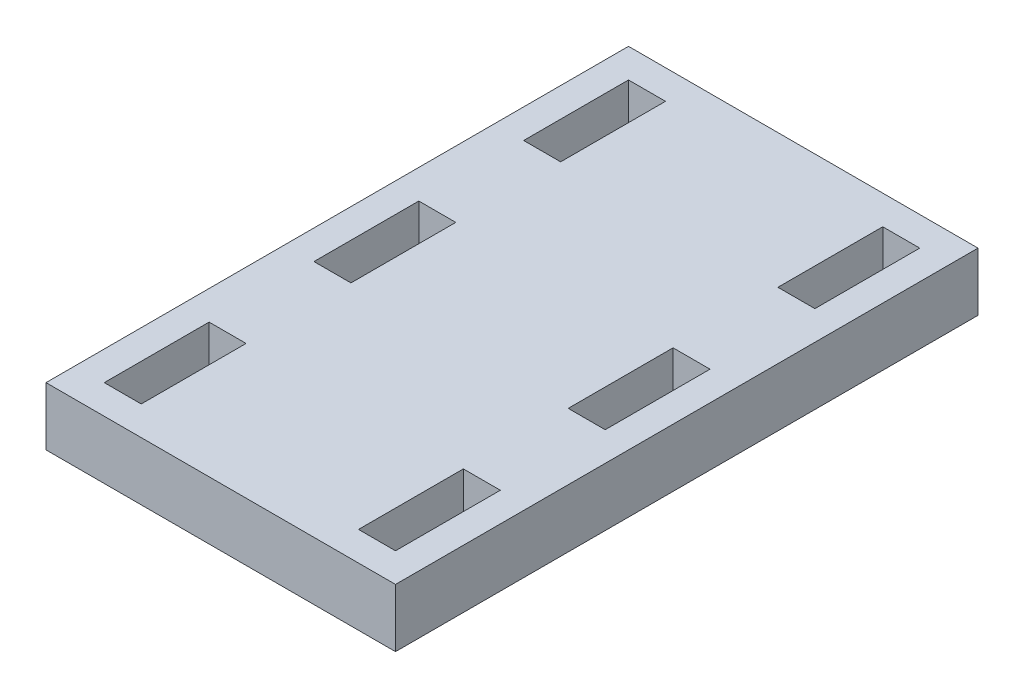
SolidWorks part; units mm, degrees
ref_plane "Front Plane" through (0, 0, 0) normal (0, 0, 1) x (1, 0, 0)
ref_plane "Top Plane" through (0, 0, 0) normal (0, 1, 0) x (1, 0, 0)
ref_plane "Right Plane" through (0, 0, 0) normal (1, 0, 0) x (0, 0, -1)
sketch "Sketch1" plane through (0, 0, 0) normal (0, 1, 0) x (1, 0, 0)
  line L0 (30, 100) -> (30, 0) construction
  line L1 (0, 0) -> (60, 0) construction
  line L2 (0, 0) -> (0, 100) construction
  line L3 (0, 100) -> (60, 100) construction
  line L4 (60, 0) -> (60, 100) construction
  line L5 (5, 5) -> (11.35, 5)
  line L6 (5, 5) -> (5, 23)
  line L7 (5, 23) -> (11.35, 23)
  line L8 (11.35, 5) -> (11.35, 23)
  line L9 (5, 41) -> (11.35, 41)
  line L10 (5, 41) -> (5, 59)
  line L11 (5, 59) -> (11.35, 59)
  line L12 (11.35, 41) -> (11.35, 59)
  line L13 (5, 77) -> (11.35, 77)
  line L14 (5, 77) -> (5, 95)
  line L15 (5, 95) -> (11.35, 95)
  line L16 (11.35, 77) -> (11.35, 95)
  line L17 (48.65, 77) -> (48.65, 95)
  line L18 (55, 95) -> (48.65, 95)
  line L19 (55, 77) -> (55, 95)
  line L20 (55, 77) -> (48.65, 77)
  line L21 (55, 59) -> (48.65, 59)
  line L22 (48.65, 41) -> (48.65, 59)
  line L23 (55, 41) -> (55, 59)
  line L24 (55, 41) -> (48.65, 41)
  line L25 (55, 5) -> (48.65, 5)
  line L26 (48.65, 5) -> (48.65, 23)
  line L27 (55, 23) -> (48.65, 23)
  line L28 (55, 5) -> (55, 23)
  dimension "D1" = 100
  dimension "D2" = 60
  dimension "D3" = 18
  dimension "D4" = 6.35
  dimension "D5" = 5
  dimension "D6" = 5
  dimension "D7" = 18
  dimension "D8" = 18
sketch "Sketch2" plane through (0, 0, 0) normal (0, 1, 0) x (1, 0, 0)
  line L1 (0, 0) -> (60, 0)
  line L2 (0, 0) -> (0, 100)
  line L3 (0, 100) -> (60, 100)
  line L4 (60, 0) -> (60, 100)
extrude "Boss-Extrude1" add sketch "Sketch2" along normal blind 10
extrude "Cut-Extrude1" cut sketch "Sketch1" along normal blind 10
